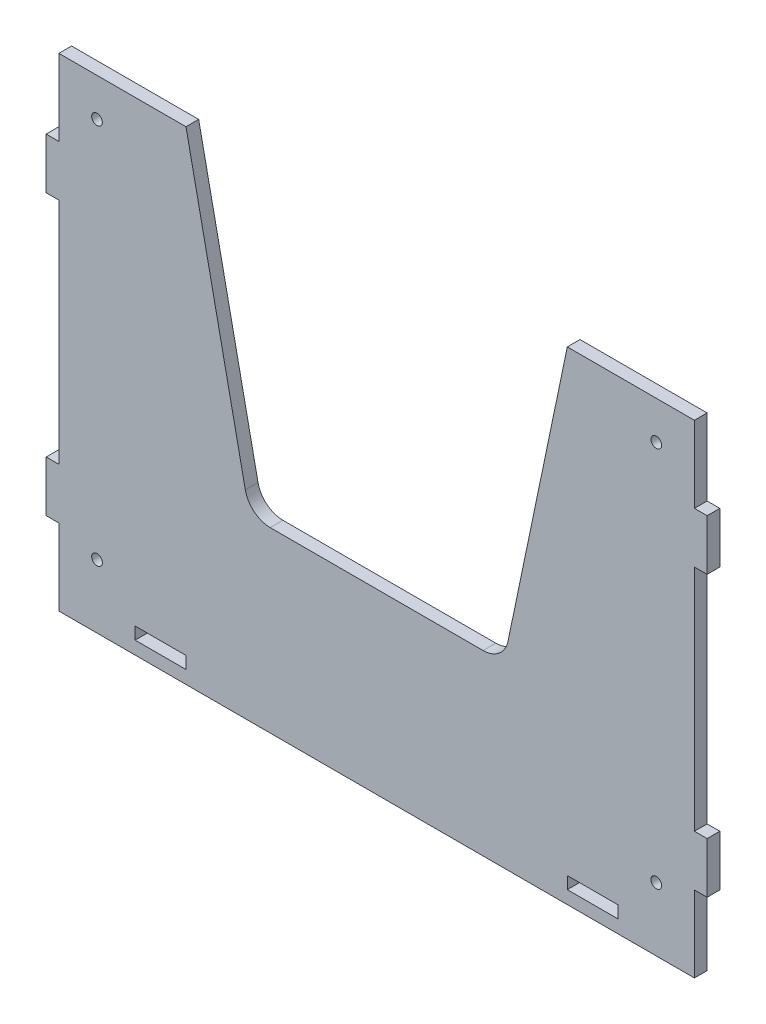
SolidWorks part; units mm, degrees
ref_plane "Front Plane" through (0, 0, 0) normal (0, 0, 1) x (1, 0, 0)
ref_plane "Top Plane" through (0, 0, 0) normal (0, 1, 0) x (1, 0, 0)
ref_plane "Right Plane" through (0, 0, 0) normal (1, 0, 0) x (0, 0, -1)
sketch "Sketch1" plane through (0, 0, 0) normal (0, 0, 1) x (1, 0, 0)
  line L0 (-125, -10) -> (-125, 20) construction
  line L1 (125, -10) -> (-125, -10)
  line L2 (125, -10) -> (125, 20)
  line L3 (125, -10) -> (125, 20) construction
  line L4 (-125, -10) -> (-125, 20)
  line L5 (125, 180) -> (75, 180)
  line L6 (75, 180) -> (50, 60)
  line L7 (50, 60) -> (-50, 60)
  line L8 (-50, 60) -> (-75, 180)
  line L9 (-75, 180) -> (-125, 180)
  line L12 (95, 0) -> (95, -5) construction
  line L13 (95, -4.9) -> (75, -4.9)
  line L14 (95, -4.9) -> (95, -0.1)
  line L15 (95, -0.1) -> (75, -0.1)
  line L16 (75, -4.9) -> (75, -0.1)
  line L17 (75, 0) -> (75, -5) construction
  line L18 (95, 0) -> (75, 0) construction
  line L19 (-75, 0) -> (-75, -5) construction
  line L20 (-75, -4.9) -> (-95, -4.9)
  line L21 (-75, -4.9) -> (-75, -0.1)
  line L22 (-75, -0.1) -> (-95, -0.1)
  line L23 (-95, -4.9) -> (-95, -0.1)
  line L24 (-95, 0) -> (-95, -5) construction
  line L25 (-75, 0) -> (-95, 0) construction
  line L26 (-130, -10) -> (-130, 20) construction
  line L27 (-125, 20) -> (-130, 20)
  line L28 (130, -10) -> (130, 20) construction
  line L29 (-125, 40) -> (-130, 40)
  line L30 (-130, 20) -> (-130, 40)
  line L31 (-125, 150) -> (-125, 180)
  line L32 (-125, 130) -> (-130, 130)
  line L33 (-125, 40) -> (-125, 130)
  line L34 (-125, 150) -> (-130, 150)
  line L35 (-130, 130) -> (-130, 150)
  line L36 (125, 40) -> (130, 40)
  line L38 (125, 20) -> (130, 20)
  line L39 (130, 40) -> (130, 20)
  line L40 (125, 150) -> (125, 180)
  line L41 (125, 150) -> (130, 150)
  line L42 (125, 40) -> (125, 130)
  line L43 (125, 130) -> (130, 130)
  line L44 (130, 150) -> (130, 130)
  dimension "D1" = 50
  dimension "D2" = 50
  dimension "D3" = 100
  dimension "D4" = 50
  dimension "D5" = 190
  dimension "D6" = 70
  dimension "D7" = 4.8
  dimension "D8" = 0.1
  dimension "D9" = 4.8
  dimension "D10" = 0.1
  dimension "D11" = 20
  dimension "D12" = 20
  dimension "D13" = 30
  dimension "D14" = 30
  dimension "D15" = 20
  dimension "D16" = 20
  dimension "D17" = 30
  dimension "D18" = 30
extrude "Boss-Extrude1" add sketch "Sketch1" along normal blind 5
fillet "Fillet1" radius 10 2 edges at (50, 60, 2.5) (-50, 60, 2.5)
sketch "Sketch2" plane through (0, 0, 5) normal (0, 0, 1) x (1, 0, 0)
  line L0 (-125, -10) -> (125, -10) construction
  line L1 (-125, 20) -> (-125, -10) construction
  line L2 (125, -10) -> (125, 20) construction
  line L4 (-75, 180) -> (-125, 180) construction
  line L5 (125, 180) -> (75, 180) construction
  circle A0 centre (-110, 15) radius 2.1
  circle A1 centre (110, 15) radius 2.1
  circle A2 centre (110, 165) radius 2.1
  circle A3 centre (-110, 165) radius 2.1
  dimension "D1" = 4.2
  dimension "D2" = 4.2
  dimension "D3" = 25
  dimension "D5" = 25
  dimension "D6" = 15
  dimension "D7" = 4.2
  dimension "D8" = 4.2
  dimension "D9" = 15
  dimension "D4" = 15
  dimension "D10" = 15
extrude "Cut-Extrude1" cut sketch "Sketch2" against normal blind 5
